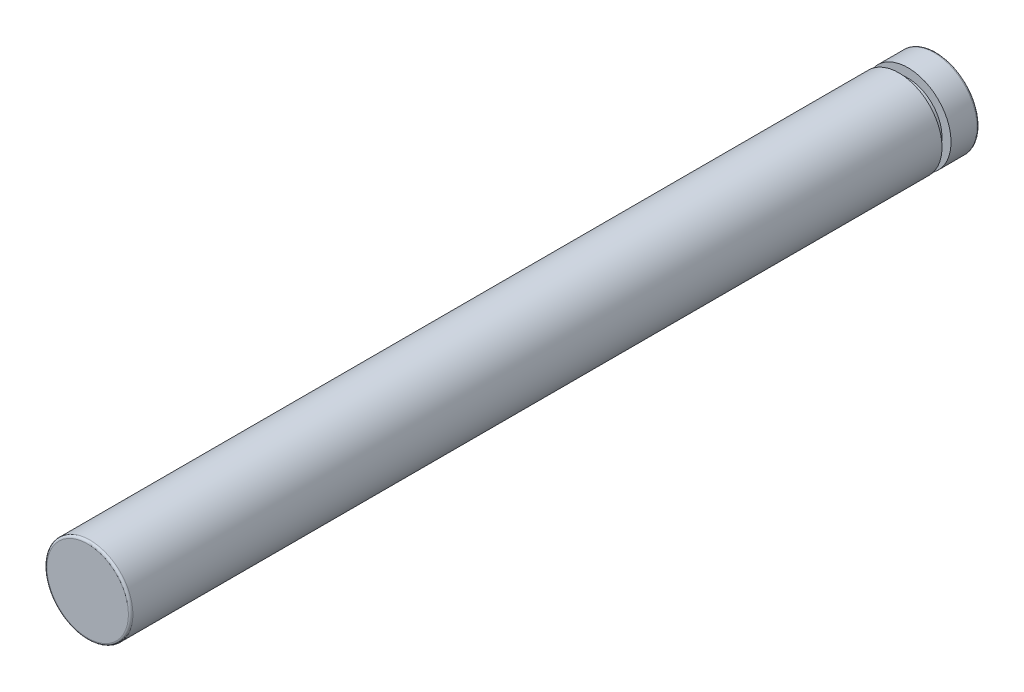
SolidWorks part; units mm, degrees
ref_plane "Front Plane" through (0, 0, 0) normal (0, 0, 1) x (1, 0, 0)
ref_plane "Top Plane" through (0, 0, 0) normal (0, 1, 0) x (1, 0, 0)
ref_plane "Right Plane" through (0, 0, 0) normal (1, 0, 0) x (0, 0, -1)
sketch "Sketch1" plane through (0, 0, 0) normal (0, 0, 1) x (1, 0, 0)
  circle A0 centre (0, 0) radius 4.826
  dimension "D1" = 9.652
extrude "Boss-Extrude1" add sketch "Sketch1" along normal mid plane 95.25
sketch "Sketch2" plane through (0, 0, 0) normal (0, 1, 0) x (1, 0, 0)
  line L0 (-4.826, 47.625) -> (-4.826, -47.625) construction
  line L1 (0, 52.0124) -> (0, 34.1988) construction
  line L2 (-4.826, 44.45) -> (-3.81, 44.45)
  line L3 (-4.826, 44.45) -> (-4.826, 43.434)
  line L4 (-4.826, 43.434) -> (-3.81, 43.434)
  line L5 (-3.81, 44.45) -> (-3.81, 43.434)
  line L6 (4.826, 47.625) -> (-4.826, 47.625) construction
  dimension "D1" = 1.016
  dimension "D2" = 7.62
  dimension "D3" = 3.175
revolve "Cut-Revolve1" cut sketch "Sketch2" angle 360 about L1
fillet "Fillet1" radius 0.254 2 edges at (4.826, 0, 47.625) (4.826, 0, -47.625)
